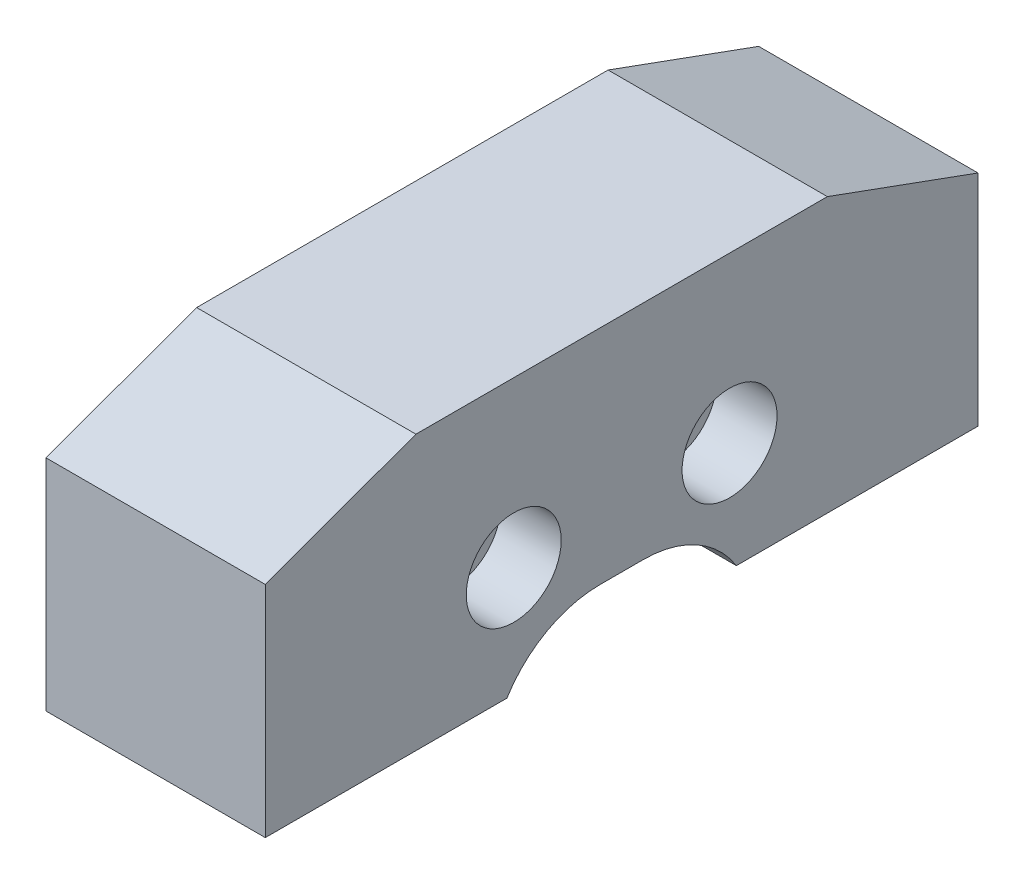
SolidWorks part; units mm, degrees
material "Low Carbon Steel"
ref_plane "Front Plane" through (0, 0, 0) normal (0, 0, 1) x (1, 0, 0)
ref_plane "Top Plane" through (0, 0, 0) normal (0, 1, 0) x (1, 0, 0)
ref_plane "Right Plane" through (0, 0, 0) normal (1, 0, 0) x (0, 0, -1)
sketch "Sketch1" plane through (0, 0, 0) normal (1, 0, 0) x (0, 0, -1)
  line L0 (-41.275, 0) -> (41.275, 0)
  line L1 (41.275, 0) -> (41.275, 25.4)
  line L2 (41.275, 25.4) -> (23.8285, 31.75)
  line L3 (23.8285, 31.75) -> (-23.8285, 31.75)
  line L4 (-41.275, 25.4) -> (-41.275, 0)
  line L5 (-23.8285, 31.75) -> (-41.275, 25.4)
  dimension "D1" = 20
  dimension "D2" = 25.4
  dimension "D3" = 31.75
  dimension "D4" = 82.55
extrude "Boss-Extrude1" add sketch "Sketch1" along normal mid plane 25.4
hole_wizard "CBORE for M6 Hex Socket Head Cap Screw1" positions "Sketch4" profile "Sketch3" counterbore size "M6" standard "Peddi DIN" end condition through all
sketch "Sketch4" plane through (12.7, 13.3426, -21.3734) normal (-1, 0, 0) x (0, 1, 0)
  line L0 (-0.6426, -8.8734) -> (-0.6426, -33.8734) construction
  line L1 (-0.6426, -33.8734) -> (-0.6426, -62.6484) construction
  line L6 (12.0574, -62.6484) -> (-13.3426, -62.6484) construction
  line L7 (-13.3426, -21.3734) -> (-0.6426, -21.3734) construction
  point P0 (-0.6426, -33.8734)
  point P2 (-0.6426, -8.8734)
  dimension "D1" = 25
sketch "Sketch3" plane through (12.7, 12.7, 12.5) normal (0, 1, 0) x (0, 0, -1)
  line L0 (0, 0) -> (0, 25.4)
  line L1 (0, 25.4) -> (3.3, 25.4)
  line L3 (3.3, 25.4) -> (3.3, 7)
  line L4 (3.3, 7) -> (5.5, 7)
  line L5 (5.5, 7) -> (5.5, 0)
  line L7 (5.5, 0) -> (0, 0)
  line L11 (0, -6.35) -> (0, 107.95) construction
  dimension "Thru Hole Dia." = 6.6
  dimension "Thru Hole Depth" = 25.4
  dimension "C'Bore Dia." = 11
  dimension "C'Bore Depth" = 7
sketch "Sketch5" plane through (12.7, 0, 0) normal (1, 0, 0) x (0, 0, -1)
  line L0 (15.2, -15) -> (15.2, -6.7)
  line L2 (2.5, 6) -> (-2.5, 6)
  line L3 (-15.2, -6.7) -> (-15.2, -15)
  line L4 (-15.2, -15) -> (15.2, -15)
  line L5 (0, 6) -> (0, 0) construction
  line L6 (-41.275, 0) -> (41.275, 0) construction
  circle A0 centre (5, -2.3) radius 7.5 construction
  circle A1 centre (12.5, 12.7) radius 3.3 construction
  circle A2 centre (12.5, 12.7) radius 5.5 construction
  arc A3 (-2.5, 6) -> (-15.2, -6.7) centre (-2.5, -6.7) ccw
  arc A4 (15.2, -6.7) -> (2.5, 6) centre (2.5, -6.7) ccw
  dimension "D1" = 15
  dimension "D3" = 15
  dimension "D4" = 12.7
  dimension "D2" = 7.5
  dimension "D5" = 6
  dimension "D6" = 90
  dimension "D7" = 90
  dimension "D8" = 5
  dimension "D9" = 15
extrude "Cut-Extrude1" cut sketch "Sketch5" against normal through all
